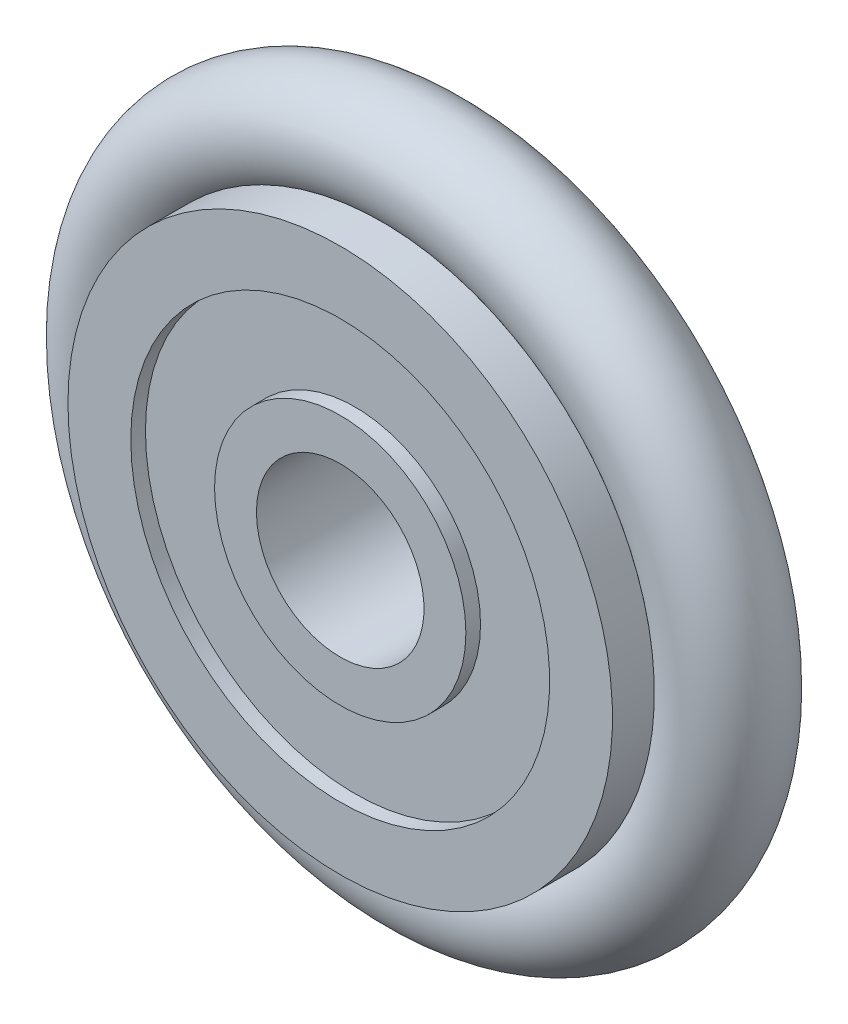
SolidWorks part; units mm, degrees
other "Bearing Center"
other "O-Ring"
ref_plane "Top" through (0, 0, 0) normal (0, 0, 1) x (1, 0, 0)
ref_plane "Front" through (0, 0, 0) normal (0, 1, 0) x (1, 0, 0)
ref_plane "Right" through (0, 0, 0) normal (1, 0, 0) x (0, 0, -1)
sketch "Sketch1" plane through (0, 0, 0) normal (0, 1, 0) x (1, 0, 0)
  line L0 (2, 2) -> (2, -2)
  line L1 (2, -2) -> (3, -2)
  line L2 (3, -2) -> (3, -1.65)
  line L3 (3, -1.65) -> (5, -1.65)
  line L4 (5, -1.65) -> (5, -2)
  line L5 (5, -2) -> (6.5, -2)
  line L6 (6.5, -2) -> (6.5, -1)
  line L7 (0, 2) -> (0, -2) construction
  line L8 (0, 2) -> (2, 2) construction
  line L9 (0, -2) -> (2, -2) construction
  line L10 (0, 0) -> (2, 0) construction
  line L11 (6.5, 2) -> (6.5, 1)
  line L12 (5, 2) -> (6.5, 2)
  line L13 (5, 1.65) -> (5, 2)
  line L14 (3, 1.65) -> (5, 1.65)
  line L15 (3, 2) -> (3, 1.65)
  line L16 (2, 2) -> (3, 2)
  arc A0 (6.5, -1) -> (6.5, 1) centre (7.25, 0) cw
  point P11 (0, 0)
  dimension "D8" = 1.25
  dimension "D1" = 4
  dimension "D2" = 1
  dimension "D3" = 2
  dimension "D4" = 6.5
  dimension "D5" = 2
  dimension "D6" = 1
  dimension "D7" = 0.35
revolve "Revolve1" add sketch "Sketch1" angle 360 about L7
sketch "Sketch6" plane through (0, 0, 0) normal (0, 1, 0) x (1, 0, 0)
  line L0 (0, 0) -> (0, 5) construction
  circle A0 centre (7.25, 0) radius 1.25
  dimension "D1" = 2.5
  dimension "D2" = 7.25
  dimension "D3" = 5
revolve "O-Ring Revolve" add sketch "Sketch6" angle 360 about L0
